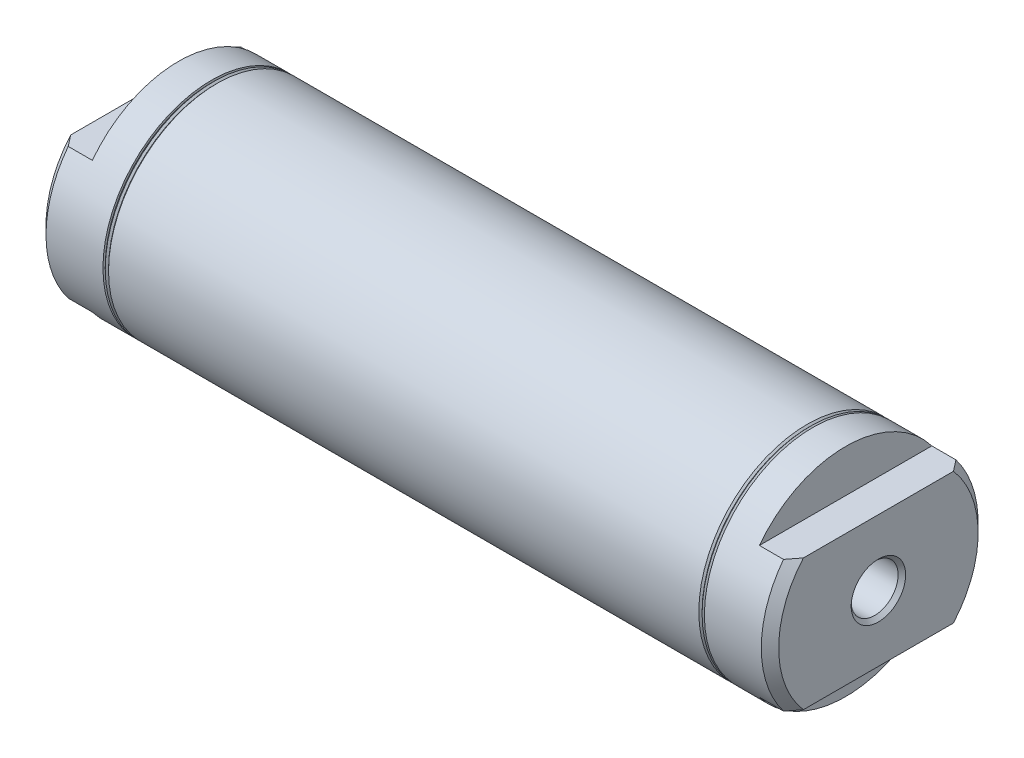
SolidWorks part; units mm, degrees
ref_plane "Front Plane" through (0, 0, 0) normal (0, 0, 1) x (1, 0, 0)
ref_plane "Top Plane" through (0, 0, 0) normal (0, 1, 0) x (1, 0, 0)
ref_plane "Right Plane" through (0, 0, 0) normal (1, 0, 0) x (0, 0, -1)
ref_plane "Plane1" through (0, 0, 0) normal (0, 0, -1) x (-1, 0, 0)
sketch "Sketch1" plane through (0, 0, 0) normal (0, 0, -1) x (-1, 0, 0)
  line L0 (-176.9872, 26.1874) -> (-176.9872, 0)
  line L1 (-176.9872, 0) -> (0, 0)
  line L2 (0, 0) -> (0, 26.1874)
  line L3 (0, 26.1874) -> (-15.8496, 26.1874)
  line L4 (-15.8496, 26.1874) -> (-15.8496, 25.6327)
  line L5 (-15.8496, 25.6327) -> (-16.4043, 26.1874)
  line L6 (-16.4043, 26.1874) -> (-16.8006, 25.7912)
  line L7 (-16.8006, 25.7912) -> (-17.1968, 26.1874)
  line L8 (-17.1968, 26.1874) -> (-159.7904, 26.1874)
  line L9 (-159.7904, 26.1874) -> (-160.1866, 25.7912)
  line L10 (-160.1866, 25.7912) -> (-160.5829, 26.1874)
  line L11 (-160.5829, 26.1874) -> (-161.1376, 25.6327)
  line L12 (-161.1376, 25.6327) -> (-161.1376, 26.1874)
  line L13 (-161.1376, 26.1874) -> (-176.9872, 26.1874)
  line L14 (-176.9872, 0) -> (0, 0) construction
revolve "Revolve1" add sketch "Sketch1" angle 360 about L14
sketch "Sketch2" plane through (0, 0, 0) normal (-1, 0, 0) x (0, 0, 1)
  line L0 (-20.827, 15.875) -> (20.827, 15.875)
  arc A0 (20.827, 15.875) -> (-20.827, 15.875) centre (0, 0) ccw
extrude "Cut-Extrude1" cut sketch "Sketch2" against normal blind 7.9248
sketch "Sketch3" plane through (0, 0, 0) normal (-1, 0, 0) x (0, 0, 1)
  line L0 (20.827, -15.875) -> (-20.827, -15.875)
  arc A0 (-20.827, -15.875) -> (20.827, -15.875) centre (0, 0) ccw
extrude "Cut-Extrude2" cut sketch "Sketch3" against normal blind 7.9248
sketch "Sketch4" plane through (176.9872, 0, 0) normal (1, 0, 0) x (0, 0, -1)
  line L0 (-20.827, 15.875) -> (20.827, 15.875)
  arc A0 (20.827, 15.875) -> (-20.827, 15.875) centre (0, 0) ccw
extrude "Cut-Extrude3" cut sketch "Sketch4" against normal blind 7.9248
sketch "Sketch5" plane through (176.9872, 0, 0) normal (1, 0, 0) x (0, 0, -1)
  line L0 (20.827, -15.875) -> (-20.827, -15.875)
  arc A0 (-20.827, -15.875) -> (20.827, -15.875) centre (0, 0) ccw
extrude "Cut-Extrude4" cut sketch "Sketch5" against normal blind 7.9248
hole_wizard "M10 Clearance Hole1" positions "Sketch7" profile "Sketch6" hole size "M10" standard "ANSI Metric"
sketch "Sketch7" plane through (176.9872, 0, 0) normal (1, 0, 0) x (0, 0, -1)
  point P0 (0, 0)
sketch "Sketch6" plane through (176.9872, 0, 0) normal (0, 1, 0) x (0, 0, -1)
  line L0 (0, 0) -> (0, 9.5098)
  line L1 (0, 9.5098) -> (5.675, 9.5098)
  line L2 (5.675, 9.5098) -> (5.675, 0)
  line L5 (5.675, 0) -> (0, 0)
  line L10 (0, 9.5098) -> (-5.675, 9.5098) construction
  line L11 (0, -6.35) -> (0, 107.95) construction
  dimension "Hole Dia." = 11.35
  dimension "Hole Depth" = 9.5098
  dimension "Drill Angle" = 180
hole_wizard "M10 Clearance Hole2" positions "Sketch9" profile "Sketch8" hole size "M10" standard "ANSI Metric"
sketch "Sketch9" plane through (0, 0, 0) normal (-1, 0, 0) x (0, 0, 1)
  point P0 (0, 0)
sketch "Sketch8" plane through (0, 0, 0) normal (0, 1, 0) x (0, 0, 1)
  line L0 (0, 0) -> (0, 9.5098)
  line L1 (0, 9.5098) -> (5.675, 9.5098)
  line L2 (5.675, 9.5098) -> (5.675, 0)
  line L5 (5.675, 0) -> (0, 0)
  line L10 (0, 9.5098) -> (-5.675, 9.5098) construction
  line L11 (0, -6.35) -> (0, 107.95) construction
  dimension "Hole Dia." = 11.35
  dimension "Hole Depth" = 9.5098
  dimension "Drill Angle" = 180
chamfer "Chamfer1" distance 2.095 angle 45 4 edges at (0, 0, 26.1874) (0, 0, -26.1874) (176.9872, 0, 26.1874) (176.9872, 0, -26.1874)
chamfer "Chamfer2" distance 0.9035 angle 45 2 edges at (176.9872, 0, -5.675) (0, 0, 5.675)
